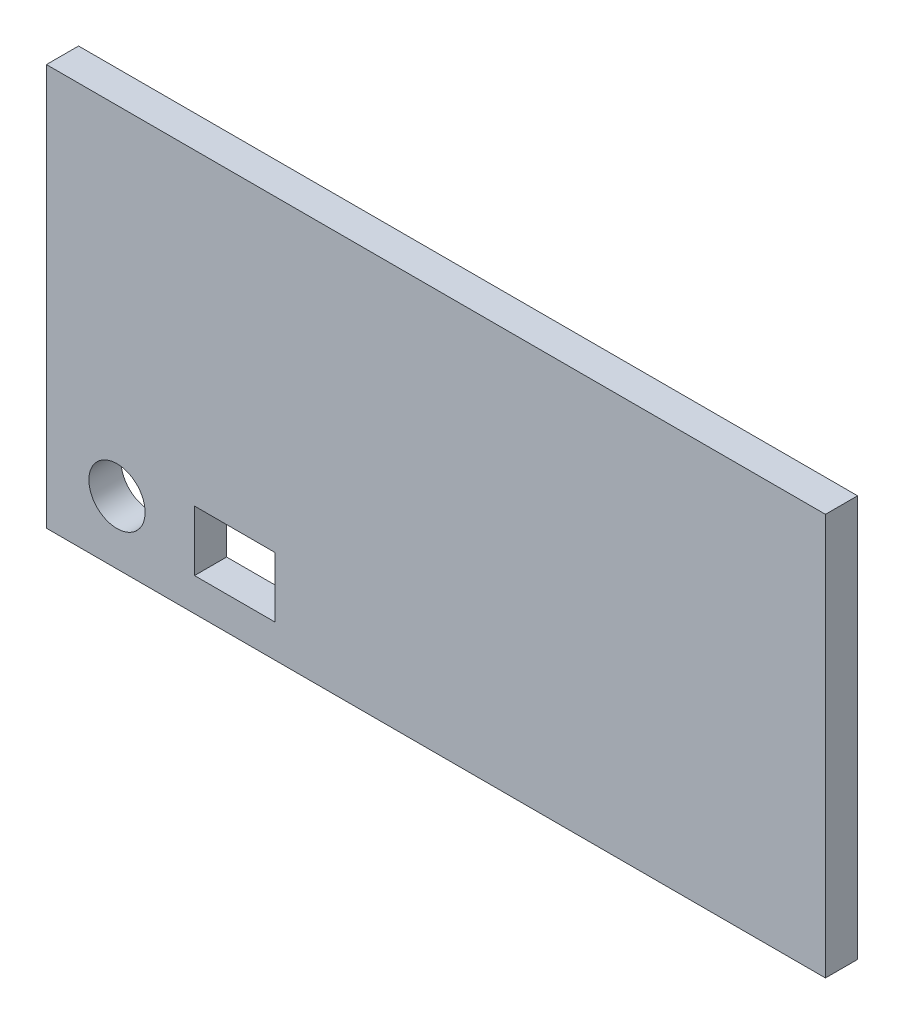
SolidWorks part; units mm, degrees
ref_plane "前视基准面" through (0, 0, 0) normal (0, 0, 1) x (1, 0, 0)
ref_plane "上视基准面" through (0, 0, 0) normal (0, 1, 0) x (1, 0, 0)
ref_plane "右视基准面" through (0, 0, 0) normal (1, 0, 0) x (0, 0, -1)
sketch "草图1" plane through (0, 0, 0) normal (0, 0, 1) x (1, 0, 0)
  line L1 (-104.7143, 58.75) -> (89.2857, 58.75)
  line L2 (-104.7143, 58.75) -> (-104.7143, -41.25)
  line L3 (-104.7143, -41.25) -> (89.2857, -41.25)
  line L4 (89.2857, 58.75) -> (89.2857, -41.25)
  line L5 (-67.8394, -18.0242) -> (-47.8394, -18.0242)
  line L6 (-67.8394, -18.0242) -> (-67.8394, -33.0242)
  line L7 (-67.8394, -33.0242) -> (-47.8394, -33.0242)
  line L8 (-47.8394, -18.0242) -> (-47.8394, -33.0242)
  circle A0 centre (-87.1429, -25.5357) radius 7
  point P10 (11.4286, -17.3214)
  point P11 (-87.1429, -25.5357)
  point P12 (-46.7857, -32.6786)
  point P13 (-47.8394, -33.0242)
  dimension "D3" = 14
  dimension "D1" = 100
  dimension "D2" = 194
  dimension "D4" = 20
  dimension "D5" = 15
extrude "凸台-拉伸1" add sketch "草图1" along normal blind 8
